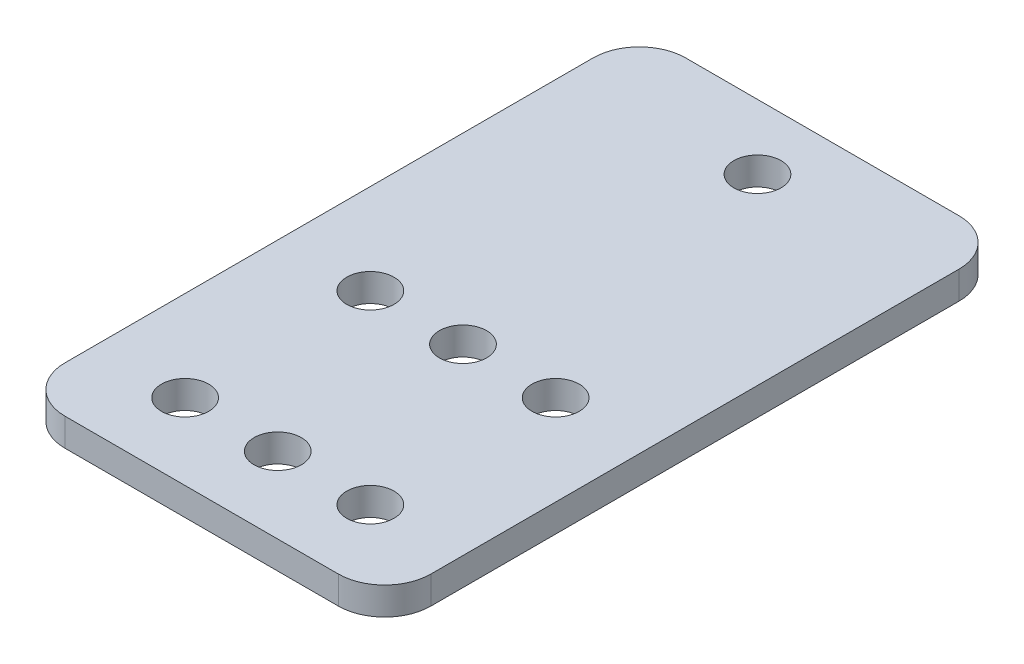
SolidWorks part; units mm, degrees
ref_plane "Front Plane" through (0, 0, 0) normal (0, 0, 1) x (1, 0, 0)
ref_plane "Top Plane" through (0, 0, 0) normal (0, 1, 0) x (1, 0, 0)
ref_plane "Right Plane" through (0, 0, 0) normal (1, 0, 0) x (0, 0, -1)
sketch "Sketch1" plane through (0, 0, 0) normal (0, 1, 0) x (1, 0, 0)
  line L1 (-19.75, -33.5) -> (19.75, -33.5)
  line L2 (-19.75, -33.5) -> (-19.75, 33.5)
  line L3 (-19.75, 33.5) -> (19.75, 33.5)
  line L4 (19.75, -33.5) -> (19.75, 33.5)
  line L5 (-19.75, -33.5) -> (19.75, 33.5) construction
  line L6 (-19.75, 33.5) -> (19.75, -33.5) construction
  point P0 (0, 0)
  dimension "D1" = 67
  dimension "D2" = 39.5
extrude "Boss-Extrude1" add sketch "Sketch1" along normal blind 3
sketch "Sketch2" plane through (0, 3, 0) normal (0, 1, 0) x (1, 0, 0)
  line L0 (0, 33.5) -> (0, -33.5) construction
  line L1 (19.75, 33.5) -> (-19.75, 33.5) construction
  line L2 (-19.75, -33.5) -> (19.75, -33.5) construction
  line L3 (-19.75, -25.29) -> (19.75, -25.29) construction
  line L4 (-19.75, 33.5) -> (-19.75, -33.5) construction
  line L5 (19.75, -33.5) -> (19.75, 33.5) construction
  line L6 (-19.75, -5.29) -> (19.75, -5.29) construction
  circle A0 centre (0, -5.29) radius 2.55
  circle A1 centre (0, -25.29) radius 2.55
  circle A2 centre (-10, -5.29) radius 2.55
  circle A3 centre (-10, -25.29) radius 2.55
  circle A4 centre (0, 26.5) radius 2.55
  circle A5 centre (10, -25.29) radius 2.55
  circle A6 centre (10, -5.29) radius 2.55
  dimension "D3" = 5.1
  dimension "D4" = 7
  dimension "D5" = 5.1
  dimension "D6" = 9.75
  dimension "D7" = 5.1
  dimension "D8" = 9.75
  dimension "D9" = 5.1
  dimension "D10" = 5.1
  dimension "D1" = 8.21
  dimension "D2" = 28.21
extrude "Cut-Extrude1" cut sketch "Sketch2" against normal through all
fillet "Fillet1" radius 5 4 edges at (-19.75, 1.5, 33.5) (19.75, 1.5, 33.5) (-19.75, 1.5, -33.5) (19.75, 1.5, -33.5)
